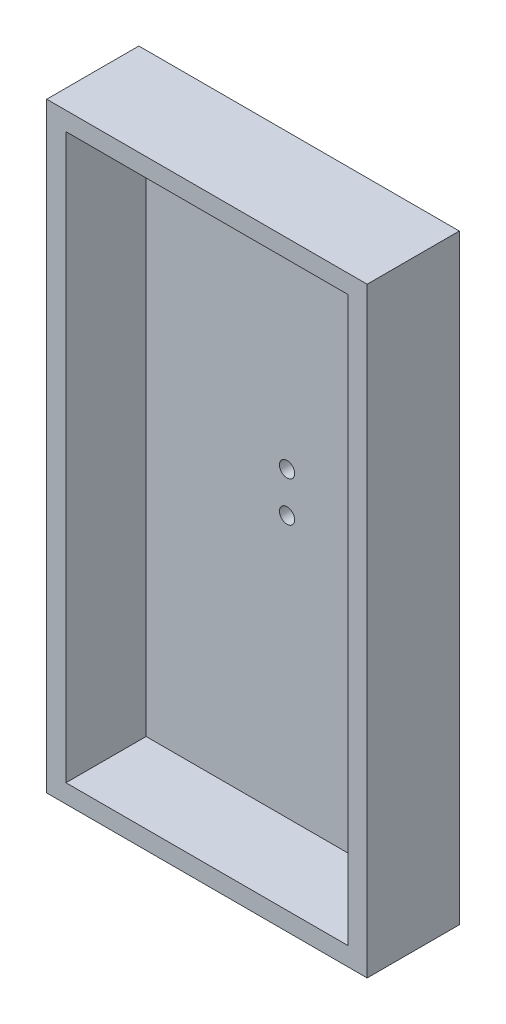
SolidWorks part; units mm, degrees
ref_plane "정면" through (0, 0, 0) normal (0, 0, 1) x (1, 0, 0)
ref_plane "윗면" through (0, 0, 0) normal (0, 1, 0) x (1, 0, 0)
ref_plane "우측면" through (0, 0, 0) normal (1, 0, 0) x (0, 0, -1)
sketch "스케치1" plane through (0, 0, 0) normal (0, 0, 1) x (1, 0, 0)
  line L1 (-40, 75) -> (40, 75)
  line L2 (-40, 75) -> (-40, -75)
  line L3 (-40, -75) -> (40, -75)
  line L4 (40, 75) -> (40, -75)
  line L5 (-40, 75) -> (40, -75) construction
  line L6 (-40, -75) -> (40, 75) construction
  point P0 (0, 0)
  dimension "D1" = 80
  dimension "D2" = 150
extrude "보스-돌출1" add sketch "스케치1" along normal blind 3
sketch "스케치2" plane through (0, 0, 0) normal (0, 0, 1) x (1, 0, 0)
  line L1 (-6, 11) -> (6, 11)
  line L2 (-6, 11) -> (-6, -11)
  line L3 (-6, -11) -> (6, -11)
  line L4 (6, 11) -> (6, -11)
  line L5 (-6, 11) -> (6, -11) construction
  line L6 (-6, -11) -> (6, 11) construction
  point P0 (0, 0)
  dimension "D1" = 12
  dimension "D2" = 22
extrude "보스-돌출2" add sketch "스케치2" against normal blind 5
sketch "스케치3" plane through (0, 0, -5) normal (0, 0, -1) x (-1, 0, 0)
  line L0 (0, 0) -> (6, 0) construction
  line L1 (6, 11) -> (6, -11) construction
  line L2 (0, 5) -> (0, 0) construction
  circle A0 centre (0, 5) radius 1.9
  circle A1 centre (0, -5) radius 1.9
  dimension "D1" = 3.8
  dimension "D2" = 10
extrude "컷-돌출1" cut sketch "스케치3" against normal through all
sketch "스케치4" plane through (0, 0, 3) normal (0, 0, 1) x (1, 0, 0)
  line L1 (-40, 75) -> (40, 75)
  line L2 (-40, 75) -> (-40, -75)
  line L3 (-40, -75) -> (40, -75)
  line L4 (40, 75) -> (40, -75)
  line L5 (-40, 75) -> (40, -75) construction
  line L6 (-40, -75) -> (40, 75) construction
  line L7 (-35.1912, 70.3823) -> (35.1912, 70.3823)
  line L8 (-35.1912, 70.3823) -> (-35.1912, -70.3823)
  line L9 (-35.1912, -70.3823) -> (35.1912, -70.3823)
  line L10 (35.1912, 70.3823) -> (35.1912, -70.3823)
  line L11 (-35.1912, 70.3823) -> (35.1912, -70.3823) construction
  line L12 (-35.1912, -70.3823) -> (35.1912, 70.3823) construction
  point P0 (0, 0)
  point P7 (0, 0)
extrude "보스-돌출3" add sketch "스케치4" along normal blind 20
